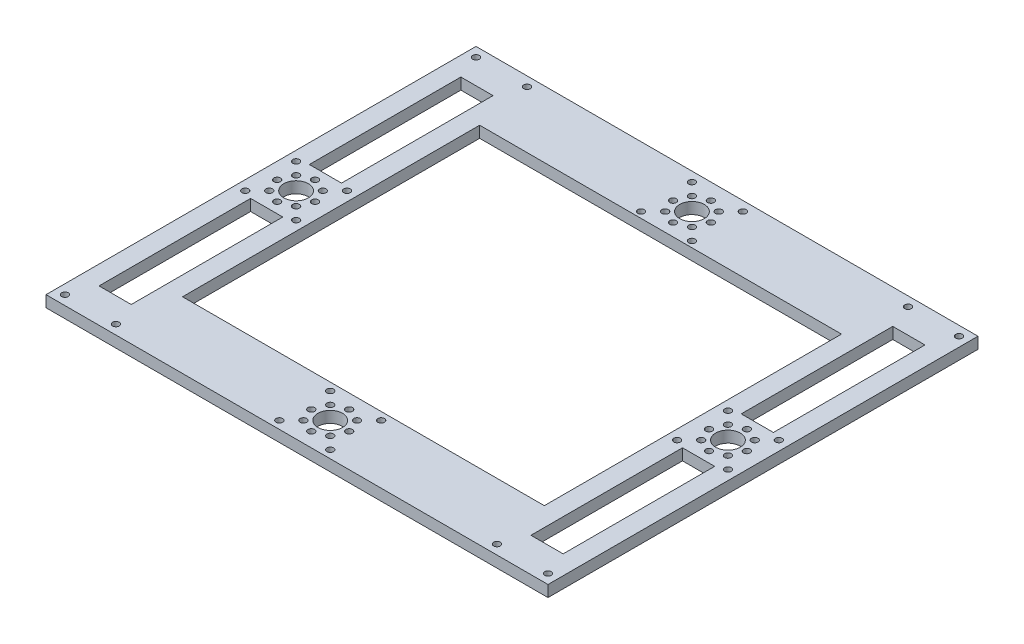
SolidWorks part; units mm, degrees
ref_plane "Plan de face" through (0, 0, 0) normal (0, 0, 1) x (1, 0, 0)
ref_plane "Plan de dessus" through (0, 0, 0) normal (0, 1, 0) x (1, 0, 0)
ref_plane "Plan de droite" through (0, 0, 0) normal (1, 0, 0) x (0, 0, -1)
sketch "Esquisse1" plane through (0, 0, 0) normal (0, 1, 0) x (1, 0, 0)
  line L0 (0, 0) -> (265, 0)
  line L1 (0, 0) -> (0, -227)
  line L2 (0, -227) -> (265, -227)
  line L3 (265, -227) -> (265, 0)
  line L7 (37, -35.0701) -> (228, -35.0701)
  line L8 (228, -35.0701) -> (228, -191.9299)
  line L9 (228, -191.9299) -> (37, -191.9299)
  line L10 (37, -191.9299) -> (37, -35.0701)
  line L19 (238, -98) -> (255, -98)
  line L22 (238, -18) -> (238, -98)
  line L23 (238, -18) -> (255, -18)
  line L24 (255, -18) -> (255, -98)
  line L29 (238, -209) -> (238, -129)
  line L30 (238, -209) -> (255, -209)
  line L31 (255, -209) -> (255, -129)
  line L32 (238, -129) -> (255, -129)
  line L33 (27, -18) -> (27, -98)
  line L34 (27, -18) -> (10, -18)
  line L35 (10, -18) -> (10, -98)
  line L36 (27, -98) -> (10, -98)
  line L37 (27, -209) -> (10, -209)
  line L38 (10, -209) -> (10, -129)
  line L39 (27, -129) -> (10, -129)
  line L40 (27, -209) -> (27, -129)
  circle A0 centre (246.5, -113.5) radius 6.5
  circle A1 centre (246.5, -103.5) radius 1.75
  circle A2 centre (253.5711, -106.4289) radius 1.75
  circle A3 centre (256.5, -113.5) radius 1.75
  circle A4 centre (253.5711, -120.5711) radius 1.75
  circle A5 centre (246.5, -123.5) radius 1.75
  circle A6 centre (239.4289, -120.5711) radius 1.75
  circle A7 centre (236.5, -113.5) radius 1.75
  circle A8 centre (239.4289, -106.4289) radius 1.75
  circle A9 centre (259.935, -100.065) radius 1.75
  circle A10 centre (259.935, -126.935) radius 1.75
  circle A11 centre (233.065, -100.065) radius 1.75
  circle A12 centre (233.065, -126.935) radius 1.75
  circle A13 centre (132.5, -209.465) radius 6.5
  circle A14 centre (132.5, -199.465) radius 1.75
  circle A15 centre (139.5711, -202.3939) radius 1.75
  circle A16 centre (142.5, -209.465) radius 1.75
  circle A17 centre (139.5711, -216.536) radius 1.75
  circle A18 centre (132.5, -219.465) radius 1.75
  circle A19 centre (125.4289, -216.536) radius 1.75
  circle A20 centre (122.5, -209.465) radius 1.75
  circle A21 centre (125.4289, -202.3939) radius 1.75
  circle A22 centre (145.935, -196.0299) radius 1.75
  circle A23 centre (145.935, -222.9) radius 1.75
  circle A24 centre (119.065, -196.0299) radius 1.75
  circle A25 centre (119.065, -222.9) radius 1.75
  circle A26 centre (18.514, -113.5) radius 6.5
  circle A27 centre (18.514, -103.5) radius 1.75
  circle A28 centre (25.585, -106.4289) radius 1.75
  circle A29 centre (28.514, -113.5) radius 1.75
  circle A30 centre (25.585, -120.5711) radius 1.75
  circle A31 centre (18.514, -123.5) radius 1.75
  circle A32 centre (11.4429, -120.5711) radius 1.75
  circle A33 centre (8.514, -113.5) radius 1.75
  circle A34 centre (11.4429, -106.4289) radius 1.75
  circle A35 centre (31.949, -100.065) radius 1.75
  circle A36 centre (31.949, -126.935) radius 1.75
  circle A37 centre (5.0789, -100.065) radius 1.75
  circle A38 centre (5.0789, -126.935) radius 1.75
  circle A39 centre (132.5, -18.5) radius 6.5
  circle A40 centre (132.5, -8.5) radius 1.75
  circle A41 centre (139.5711, -11.4289) radius 1.75
  circle A42 centre (142.5, -18.5) radius 1.75
  circle A43 centre (139.5711, -25.5711) radius 1.75
  circle A44 centre (132.5, -28.5) radius 1.75
  circle A45 centre (125.4289, -25.5711) radius 1.75
  circle A46 centre (122.5, -18.5) radius 1.75
  circle A47 centre (125.4289, -11.4289) radius 1.75
  circle A48 centre (145.935, -5.065) radius 1.75
  circle A49 centre (145.935, -31.935) radius 1.75
  circle A50 centre (119.065, -5.065) radius 1.75
  circle A51 centre (119.065, -31.935) radius 1.75
  circle A52 centre (260, -5) radius 1.75
  circle A53 centre (233.065, -5) radius 1.75
  circle A60 centre (260, -222) radius 1.75
  circle A61 centre (233.065, -222) radius 1.75
  circle A62 centre (5, -5) radius 1.75
  circle A63 centre (31.935, -5) radius 1.75
  circle A64 centre (5, -222) radius 1.75
  circle A65 centre (31.935, -222) radius 1.75
  dimension "D1" = 265
  dimension "D2" = 227
  dimension "D3" = 227
extrude "Boss.-Extru.1" add sketch "Esquisse1" along normal blind 6
